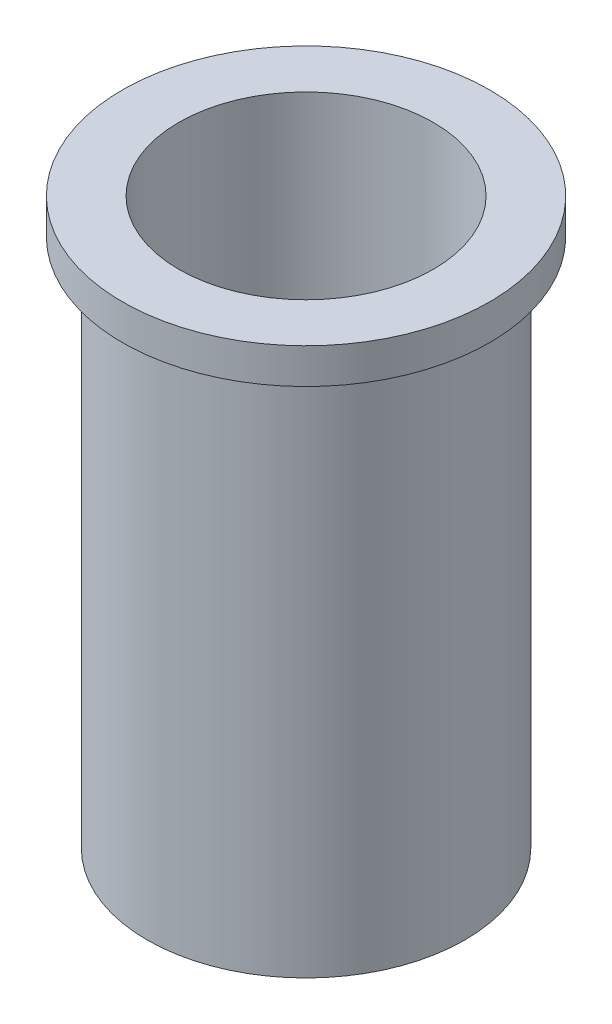
SolidWorks part; units mm, degrees
material "6061 Alloy"
ref_plane "Front Plane" through (0, 0, 0) normal (0, 0, 1) x (1, 0, 0)
ref_plane "Top Plane" through (0, 0, 0) normal (0, 1, 0) x (1, 0, 0)
ref_plane "Right Plane" through (0, 0, 0) normal (1, 0, 0) x (0, 0, -1)
sketch "Sketch1" plane through (0, 0, 0) normal (0, 0, 1) x (1, 0, 0)
  line L0 (0, 0) -> (0, 50.8) construction
  line L1 (11.4458, 50.8) -> (11.4458, 0)
  line L2 (11.4458, 0) -> (14.2875, 0)
  line L3 (14.2875, 0) -> (14.2875, 47.625)
  line L4 (14.2875, 47.625) -> (16.51, 47.625)
  line L5 (16.51, 47.625) -> (16.51, 50.8)
  line L6 (16.51, 50.8) -> (11.4458, 50.8)
  dimension "D1" = 50.8
  dimension "D2" = 28.575
  dimension "D3" = 22.8916
  dimension "D4" = 33.02
  dimension "D5" = 3.175
revolve "Revolve1" add sketch "Sketch1" angle 360 about L0
